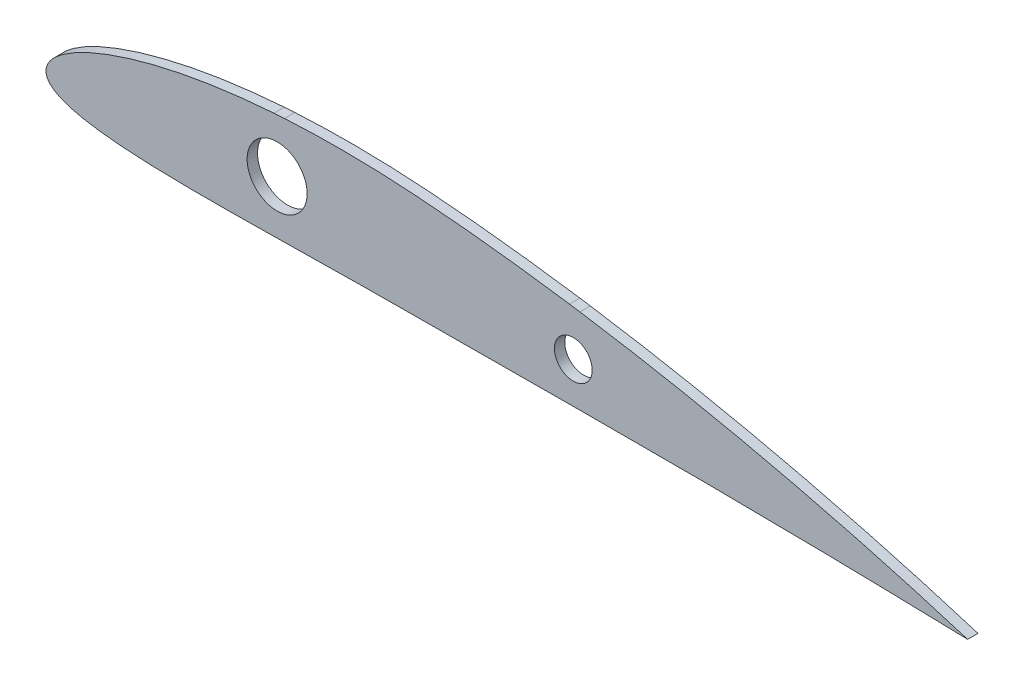
SolidWorks part; units mm, degrees
material "Фанера"
ref_plane "Front Plane" through (0, 0, 0) normal (0, 0, 1) x (1, 0, 0)
ref_plane "Top Plane" through (0, 0, 0) normal (0, 1, 0) x (1, 0, 0)
ref_plane "Right Plane" through (0, 0, 0) normal (1, 0, 0) x (0, 0, -1)
sketch "Эскиз1" plane through (0, 0, 0) normal (0, 0, 1) x (1, 0, 0)
  line L0 (150.3512, 128.259) -> (147.6767, 128.661)
  line L1 (255.981, 105.8183) -> (150.7263, 130.2251) construction
  line L2 (69.8251, 105.8135) -> (147.0441, 106.4426) construction
  line L3 (6.1919, 114.8477) -> (66.9719, 105.7712) construction
  line L4 (68.006, 135.3847) -> (6.1919, 114.8477) construction
  line L5 (68.3924, 133.4055) -> (14.7673, 115.5893) construction
  line L6 (69.8021, 107.8133) -> (147.0317, 108.4426) construction
  line L7 (147.8895, 130.6515) -> (70.8642, 135.5703) construction
  line L8 (67.001, 103.7714) -> (69.8554, 103.8137) construction
  line L9 (70.7405, 137.5665) -> (67.8703, 137.3801) construction
  line L10 (151.028, 132.2022) -> (148.1867, 132.6293) construction
  line L11 (147.0528, 104.4426) -> (149.9045, 104.4548) construction
  line L12 (147.6767, 128.661) -> (70.8653, 133.5662) construction
  line L13 (240.4166, 107.3743) -> (150.3512, 128.259) construction
  line L14 (149.8962, 106.4548) -> (255.959, 105.1887) construction
  line L15 (149.9039, 108.4548) -> (240.4166, 107.3743) construction
  line L16 (150.7263, 130.2251) -> (147.8895, 130.6515) construction
  line L17 (147.0441, 106.4426) -> (149.8962, 106.4548) construction
  line L18 (66.9719, 105.7712) -> (69.8251, 105.8135) construction
  line L19 (70.8642, 135.5703) -> (68.006, 135.3847) construction
  line L20 (67.1056, 107.7734) -> (69.8021, 107.8133) construction
  line L21 (70.8653, 133.5662) -> (68.3924, 133.4055) construction
  line L22 (147.0317, 108.4426) -> (149.9039, 108.4548) construction
  line L23 (14.7673, 115.5893) -> (67.1056, 107.7734) construction
  line L24 (150.6664, 129.8296) -> (147.8304, 130.2559)
  line L25 (70.8877, 135.171) -> (68.0343, 134.9857)
  line L26 (66.966, 106.1712) -> (69.8191, 106.2134)
  line L27 (147.0423, 106.8426) -> (149.8946, 106.8548)
  arc A0 (240.4166, 107.3743) -> (240.4166, 107.3743) centre (240.4166, 107.3743) ccw
  arc A1 (255.3129, 105.6068) -> (255.3129, 105.6068) centre (255.3129, 105.6068) ccw
  circle A2 centre (148.8681, 117.845) radius 5.1
  circle A4 centre (68.9168, 120.6369) radius 8.1
  arc A6 (256.3721, 103.1764) -> (256.8714, 107.636) centre (255.6552, 105.5145) ccw construction
  arc A8 (255.959, 105.1887) -> (255.981, 105.8183) centre (255.6552, 105.5145) ccw construction
  spline S0 degree 1 poles (147.8304, 130.2559) (70.8877, 135.171) knots 0 0 1 1 construction
  spline S1 degree 1 poles (68.0343, 134.9857) (6.5854, 114.7729) knots 0 0 1 1 construction
  spline S2 degree 1 poles (6.5854, 114.7729) (66.966, 106.1712) knots 0 0 1 1 construction
  spline S3 degree 1 poles (69.8191, 106.2134) (147.0423, 106.8426) knots 0 0 1 1 construction
  spline S4 degree 1 poles (149.8946, 106.8548) (255.3129, 105.6068) knots 0 0 1 1 construction
  spline S5 degree 1 poles (255.3129, 105.6068) (150.6664, 129.8296) knots 0 0 1 1 construction
  spline S6 degree 3 poles (147.8304, 130.2559) (141.4614, 131.1985) (128.6934, 132.8864) (112.6704, 134.4616) (99.827, 135.315) (86.964, 135.7313) (77.3083, 135.5495) (70.8877, 135.171) knots 0.429725 0.429725 0.429725 0.429725 0.504545 0.579365 0.616774 0.654184 0.729004 0.729004 0.729004 0.729004
  spline S7 degree 3 poles (68.0343, 134.9857) (62.4663, 134.5901) (54.1288, 133.7002) (43.1252, 131.8029) (34.9538, 129.9771) (26.9072, 127.676) (20.368, 125.2621) (15.3365, 122.8884) (11.7396, 120.808) (8.9915, 118.6964) (7.4817, 116.8862) (6.9154, 115.8582) (6.7079, 115.2743) (6.6255, 114.9369) (6.5854, 114.7729) knots 0.740091 0.740091 0.740091 0.740091 0.805048 0.837527 0.870006 0.902484 0.934963 0.951202 0.967442 0.983681 0.991801 0.995861 0.99789 0.99992 0.99992 0.99992 0.99992
  spline S8 degree 3 poles (6.5854, 114.7729) (6.5637, 114.6143) (6.519, 114.2854) (6.5148, 113.7109) (6.7419, 112.6615) (7.6602, 111.4099) (9.2591, 110.3083) (11.0446, 109.4874) (12.9222, 108.8501) (15.4901, 108.1728) (18.7685, 107.5586) (22.7454, 107.0432) (28.0773, 106.5574) (34.7696, 106.2135) (42.8135, 106.0372) (50.8627, 106.0061) (58.9136, 106.0623) (64.282, 106.1325) (66.966, 106.1712) knots 0.000081 0.000081 0.000081 0.000081 0.002067 0.004053 0.008026 0.01597 0.023915 0.031859 0.039804 0.047748 0.063637 0.079526 0.095416 0.127194 0.158972 0.19075 0.222528 0.254306 0.254306 0.254306 0.254306
  spline S9 degree 3 poles (69.8191, 106.2134) (76.2539, 106.311) (85.9048, 106.4721) (98.7779, 106.6108) (111.6511, 106.6495) (127.7354, 106.7325) (140.607, 106.8137) (147.0423, 106.8426) knots 0.265565 0.265565 0.265565 0.265565 0.341733 0.379817 0.417901 0.494069 0.570237 0.570237 0.570237 0.570237
  spline S10 degree 3 poles (149.8946, 106.8548) (158.6803, 106.89) (176.2516, 106.9163) (202.6097, 106.7306) (228.9647, 106.2926) (246.5305, 105.8506) (255.3129, 105.6068) knots 0.58149 0.58149 0.58149 0.58149 0.685469 0.789448 0.893427 0.997406 0.997406 0.997406 0.997406
  spline S11 degree 3 poles (255.3129, 105.6068) (246.7563, 108.2609) (229.5444, 113.257) (203.4702, 119.7998) (177.1786, 125.4044) (159.5222, 128.478) (150.6664, 129.8296) knots 0.002228 0.002228 0.002228 0.002228 0.106325 0.210423 0.31452 0.418617 0.418617 0.418617 0.418617
  spline S12 degree 3 poles (4.2245, 115.2218) (4.2126, 115.1351) (4.1901, 114.9728) (4.1369, 114.5596) (4.0997, 113.8715) (4.1934, 113.0746) (4.4478, 112.0722) (5.0329, 110.8962) (5.9577, 109.8121) (6.9592, 108.9756) (8.333, 108.0935) (10.0616, 107.291) (12.1329, 106.5788) (14.8842, 105.8458) (18.3089, 105.1999) (22.402, 104.6657) (26.4841, 104.2911) (30.5571, 104.0277) (35.978, 103.7862) (42.7402, 103.6379) (50.8379, 103.6058) (58.9249, 103.6622) (64.3084, 103.7327) (67.001, 103.7714) knots -0.000405 -0.000405 -0.000405 -0.000405 0.00059 0.001585 0.003575 0.005565 0.007555 0.011535 0.015514 0.019494 0.023474 0.031434 0.039394 0.047354 0.063273 0.079193 0.095112 0.111032 0.126952 0.158791 0.19063 0.222469 0.254308 0.254308 0.254308 0.254308 construction
  spline S13 degree 3 poles (67.8703, 137.3801) (65.0503, 137.1797) (59.4186, 136.6785) (50.9968, 135.5967) (42.6198, 134.1508) (34.309, 132.2908) (27.4644, 130.3322) (22.0663, 128.4455) (18.0689, 126.8357) (14.1437, 124.9752) (10.9598, 123.1311) (8.5154, 121.3532) (7.0522, 120.0467) (5.9644, 118.8218) (5.3324, 117.9305) (4.8996, 117.1691) (4.5854, 116.5037) (4.3875, 115.8781) (4.2866, 115.4769) (4.246, 115.3096) (4.2245, 115.2218) knots 0.740067 0.740067 0.740067 0.740067 0.772609 0.80515 0.837691 0.870232 0.902774 0.919044 0.935315 0.951586 0.967856 0.975992 0.984127 0.988195 0.992262 0.994296 0.99633 0.998364 0.999381 1.000398 1.000398 1.000398 1.000398 construction
  spline S14 degree 3 poles (148.1867, 132.6293) (141.7912, 133.5759) (128.9685, 135.2709) (112.884, 136.8527) (99.9444, 137.7126) (86.9715, 138.1325) (77.2213, 137.9485) (70.7405, 137.5665) knots 0.429706 0.429706 0.429706 0.429706 0.504536 0.579367 0.616782 0.654197 0.729027 0.729027 0.729027 0.729027 construction
  spline S15 degree 3 poles (256.8714, 107.636) (248.2169, 110.3216) (230.8173, 115.4068) (204.446, 122.039) (177.8555, 127.7216) (159.9886, 130.8346) (151.028, 132.2022) knots -0.001207 -0.001207 -0.001207 -0.001207 0.10375 0.208706 0.313663 0.418619 0.418619 0.418619 0.418619 construction
  spline S16 degree 3 poles (149.9045, 104.4548) (158.7785, 104.4903) (176.5281, 104.5165) (203.1441, 104.3248) (229.757, 103.8766) (247.5013, 103.4229) (256.3721, 103.1764) knots 0.581491 0.581491 0.581491 0.581491 0.686581 0.79167 0.89676 1.001849 1.001849 1.001849 1.001849 construction
  spline S17 degree 3 poles (69.8554, 103.8137) (76.2881, 103.9112) (85.9421, 104.0724) (98.7946, 104.2108) (111.6509, 104.2495) (127.7557, 104.3325) (140.6187, 104.4137) (147.0528, 104.4426) knots 0.265565 0.265565 0.265565 0.265565 0.341733 0.379817 0.4179 0.494068 0.570236 0.570236 0.570236 0.570236 construction
  spline S24 degree 3 poles (255.981, 105.8183) (255.1452, 106.0776) (252.7344, 106.8257) (248.4483, 108.1259) (242.96, 109.7477) (236.9465, 111.469) (230.6793, 113.2037) (224.3094, 114.9057) (217.8951, 116.5587) (211.4569, 118.157) (205.0023, 119.6987) (198.5346, 121.1828) (192.0557, 122.6086) (185.5671, 123.9752) (179.0705, 125.2817) (172.5672, 126.5268) (166.0589, 127.7093) (159.5471, 128.8277) (154.4349, 129.6536) (151.4938, 130.108) (150.7263, 130.2251) knots 0 0 0 0 0.010162 0.029313 0.052012 0.076619 0.101948 0.127526 0.153184 0.178868 0.204558 0.230246 0.255926 0.281594 0.307246 0.332878 0.358485 0.384061 0.409603 0.418619 0.418619 0.418619 0.418619 construction
  spline S25 degree 3 poles (149.8962, 106.4548) (151.0697, 106.4595) (154.5381, 106.4723) (160.2987, 106.4873) (167.1755, 106.4936) (174.0453, 106.4866) (180.9094, 106.465) (187.7693, 106.4278) (194.6263, 106.3745) (201.4814, 106.3045) (208.3355, 106.2177) (217.4659, 106.0799) (226.5694, 105.9098) (235.5825, 105.7122) (242.0508, 105.5578) (247.9425, 105.407) (252.5192, 105.2842) (255.0798, 105.2131) (255.959, 105.1887) knots 0.58149 0.58149 0.58149 0.58149 0.59538 0.622543 0.649673 0.676775 0.703855 0.730919 0.757971 0.785018 0.812062 0.839103 0.893099 0.919831 0.94581 0.969681 0.98959 1 1 1 1 construction
  spline S26 degree 3 poles (69.8251, 105.8135) (70.1857, 105.8189) (72.8406, 105.8595) (77.7874, 105.9382) (84.6559, 106.0429) (91.5023, 106.1327) (98.3304, 106.2005) (105.1587, 106.2352) (112.0058, 106.2499) (118.883, 106.2851) (125.7838, 106.3242) (132.6989, 106.366) (139.7863, 106.4072) (144.5679, 106.4315) (147.0441, 106.4426) knots 0.265565 0.265565 0.265565 0.265565 0.269834 0.296993 0.324123 0.351139 0.378036 0.404946 0.431961 0.459078 0.486347 0.513641 0.540929 0.570237 0.570237 0.570237 0.570237 construction
  spline S27 degree 3 poles (6.1919, 114.8477) (6.158, 114.6008) (6.0902, 114.1069) (6.1694, 113.3417) (6.4146, 112.5783) (6.8536, 111.8363) (7.4788, 111.1398) (8.2841, 110.4896) (9.2784, 109.8798) (10.4882, 109.2993) (11.964, 108.7389) (13.7853, 108.1919) (16.0678, 107.6555) (18.9581, 107.1364) (22.5962, 106.6558) (27.0464, 106.2459) (32.2488, 105.9348) (38.0427, 105.7329) (44.2433, 105.6313) (50.7063, 105.6105) (57.3406, 105.6492) (62.7802, 105.7125) (66.003, 105.7573) (66.9719, 105.7712) knots 0 0 0 0 0.002941 0.005884 0.009016 0.012365 0.016008 0.020037 0.024574 0.029784 0.035897 0.04324 0.052276 0.063635 0.077983 0.095698 0.11652 0.139661 0.164312 0.189919 0.216157 0.242838 0.254307 0.254307 0.254307 0.254307 construction
  spline S28 degree 3 poles (68.006, 135.3847) (66.8126, 135.2999) (63.6237, 135.0487) (58.4686, 134.5329) (52.5772, 133.7756) (46.793, 132.8557) (41.1539, 131.7728) (35.7197, 130.533) (30.584, 129.1556) (25.8745, 127.6815) (21.7278, 126.1743) (18.2359, 124.7076) (15.4053, 123.3395) (13.1621, 122.0961) (11.3946, 120.9731) (9.9961, 119.9509) (8.8828, 119.0062) (7.9974, 118.1179) (7.2991, 117.2701) (6.7718, 116.4486) (6.3879, 115.6507) (6.2553, 115.1075) (6.1919, 114.8477) knots 0.740091 0.740091 0.740091 0.740091 0.753983 0.777235 0.800246 0.822951 0.845237 0.866916 0.887662 0.906968 0.924203 0.938879 0.950932 0.960693 0.968647 0.975233 0.980795 0.985584 0.989782 0.993521 0.996902 1 1 1 1 construction
  spline S29 degree 3 poles (147.8895, 130.6515) (147.4311, 130.7194) (144.8039, 131.1052) (140.0082, 131.7785) (133.5004, 132.6198) (127.0013, 133.3854) (120.5131, 134.0729) (114.0543, 134.6743) (107.657, 135.196) (101.3381, 135.605) (95.0879, 135.8768) (88.882, 136.0122) (82.7096, 136.0098) (76.7059, 135.8678) (72.7625, 135.6822) (70.8642, 135.5703) knots 0.429724 0.429724 0.429724 0.429724 0.435104 0.460559 0.485959 0.511303 0.536552 0.561723 0.586629 0.611085 0.635251 0.659272 0.683164 0.706922 0.729004 0.729004 0.729004 0.729004 construction
  dimension "D1" = 16.2
  dimension "D2" = 10.2
  dimension "D3" = 0.4
  dimension "D5" = 2
extrude "Бобышка-Вытянуть1" add sketch "Эскиз1" along normal mid plane 2.8 contours S10 S11 L24 S6 L25 S7 S8 L26 S9 L27 A2 A4
